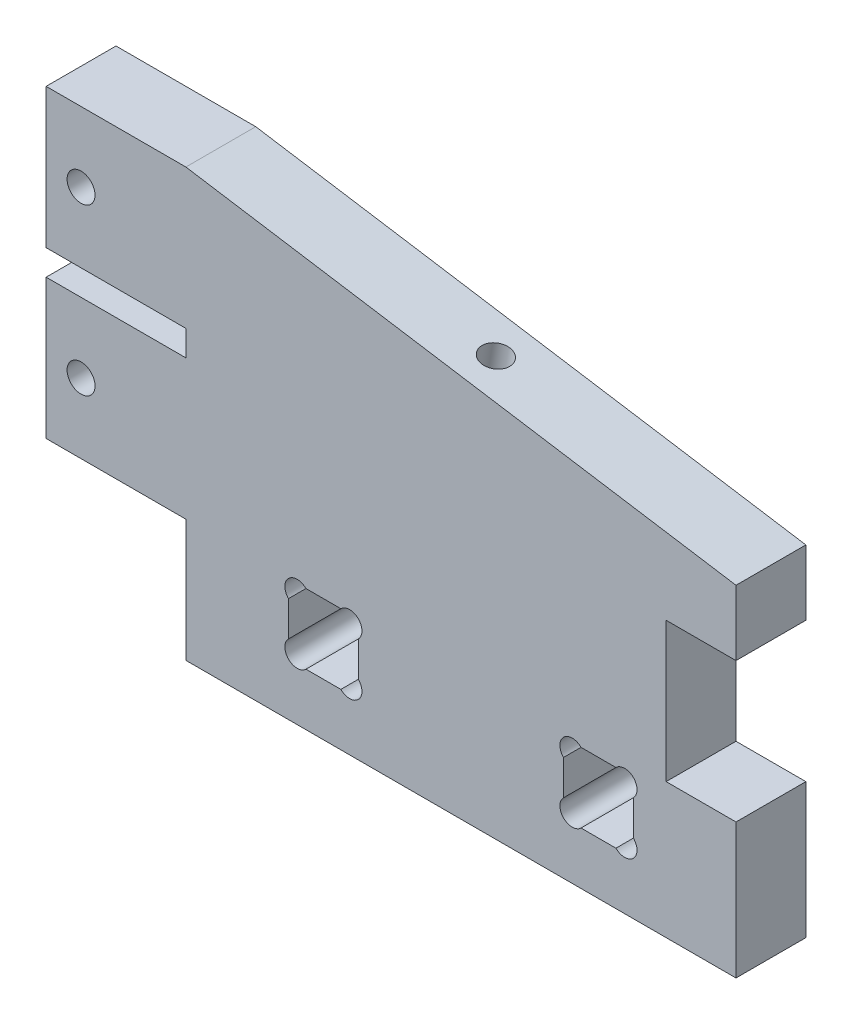
SolidWorks part; units mm, degrees
material "6061 Alloy"
ref_plane "Front" through (0, 0, 0) normal (0, 0, 1) x (1, 0, 0)
ref_plane "Top" through (0, 0, 0) normal (0, 1, 0) x (1, 0, 0)
ref_plane "Right" through (0, 0, 0) normal (1, 0, 0) x (0, 0, -1)
sketch "Sketch1" plane through (0, 0, 0) normal (0, 0, 1) x (1, 0, 0)
  line L0 (31.75, -68.1416) -> (31.75, -55.4412)
  line L1 (0, -55.4412) -> (31.75, -55.4412)
  line L2 (31.75, -68.1416) -> (131.75, -68.1416)
  line L3 (131.75, -68.1416) -> (131.75, -15.8384)
  line L4 (131.75, -15.8384) -> (31.75, 0)
  line L5 (0, -55.4412) -> (0, -30.0412)
  line L6 (0, -30.0412) -> (19.05, -30.0412)
  line L7 (31.75, 0) -> (19.05, 0)
  line L8 (19.05, -30.0412) -> (31.75, -30.0412)
  line L9 (19.05, -25.4) -> (0, -25.4)
  line L10 (19.05, 0) -> (0, 0)
  line L11 (0, -25.4) -> (0, 0)
  line L12 (31.75, -30.0412) -> (31.75, -25.4)
  line L13 (31.75, -25.4) -> (19.05, -25.4)
extrude "Boss-Extrude1" add sketch "Sketch1" along normal blind 12.7
sketch "Sketch2" plane through (0, 0, 12.7) normal (0, 0, 1) x (1, 0, 0)
  line L14 (19.05, 0) -> (19.05, -25.4) construction
  line L19 (0, -55.4412) -> (19.05, -55.4412)
  line L20 (0, -55.4412) -> (0, 0)
  line L21 (0, 0) -> (19.05, 0)
  line L23 (0, -25.4) -> (31.75, -25.4) construction
  line L24 (19.05, -12.7) -> (31.75, -12.7) construction
  line L25 (31.75, -27.7206) -> (0, -27.7206) construction
  line L26 (31.75, -25.4) -> (31.75, -30.0412) construction
  line L27 (19.05, 0) -> (19.05, -55.4412)
  circle A0 centre (25.4, -12.7) radius 2.54
  circle A1 centre (25.4, -42.7412) radius 2.54
  dimension "D1" = 5.08
extrude "Cut-Extrude2" cut sketch "Sketch2" against normal through all
sketch "Sketch3" plane through (0, 0, 12.7) normal (0, 0, 1) x (1, 0, 0)
  line L0 (131.75, -68.1416) -> (131.75, -15.8384) construction
  line L6 (31.75, -68.1412) -> (131.75, -68.1412)
  line L7 (31.75, -68.1412) -> (31.75, -81.0997)
  line L8 (31.75, -81.0997) -> (131.75, -81.0997)
  line L9 (131.75, -68.1412) -> (131.75, -81.0997)
extrude "Cut-Extrude3" cut sketch "Sketch3" against normal through all
sketch "Sketch5" plane through (0, 0, 12.7) normal (0, 0, 1) x (1, 0, 0)
  line L1 (31.75, -68.1412) -> (131.75, -68.1412)
  line L2 (31.75, -68.1412) -> (31.75, -77.6662)
  line L3 (31.75, -77.6662) -> (131.75, -77.6662)
  line L4 (131.75, -68.1412) -> (131.75, -77.6662)
  dimension "D1" = 9.525
extrude "Boss-Extrude3" add sketch "Sketch5" against normal up to surface (12.7 mm away) up to face at (45.3136, -33.9896, 0)
sketch "Sketch4" plane through (0, 0, 12.7) normal (0, 0, 1) x (1, 0, 0)
  line L6 (81.75, -58.6162) -> (81.75, -60.123) construction
  line L7 (56.75, -68.1412) -> (63.1, -68.1412)
  line L9 (56.75, -55.4412) -> (63.1, -55.4412)
  line L10 (63.1, -68.1412) -> (63.1, -55.4412)
  line L11 (56.75, -68.1412) -> (50.4, -68.1412)
  line L13 (56.75, -55.4412) -> (50.4, -55.4412)
  line L14 (50.4, -68.1412) -> (50.4, -55.4412)
  line L15 (106.75, -68.1412) -> (113.1, -68.1412)
  line L16 (113.1, -68.1412) -> (113.1, -55.4412)
  line L17 (106.75, -55.4412) -> (113.1, -55.4412)
  line L18 (106.75, -55.4412) -> (100.4, -55.4412)
  line L19 (100.4, -68.1412) -> (100.4, -55.4412)
  line L20 (106.75, -68.1412) -> (100.4, -68.1412)
  line L21 (56.75, -55.4412) -> (56.75, -68.1412) construction
  line L22 (56.75, -61.7912) -> (63.1, -61.7912) construction
  circle A0 centre (51.9875, -57.0287) radius 2.2454
  circle A1 centre (51.9875, -66.5537) radius 2.2454
  circle A2 centre (61.5125, -66.5537) radius 2.2454
  circle A3 centre (61.5125, -57.0287) radius 2.2454
  circle A4 centre (101.9875, -66.5537) radius 2.2454
  circle A5 centre (101.9875, -57.0287) radius 2.2454
  circle A6 centre (111.5125, -66.5537) radius 2.2454
  circle A7 centre (111.5125, -57.0287) radius 2.2454
  point P0 (31.75, -77.6662)
  dimension "D5" = 4.4907
  dimension "D1" = 9.525
  dimension "D2" = 12.7
  dimension "D3" = 6.35
  dimension "D4" = 6.35
  dimension "D6" = 1.5875
  dimension "D7" = 1.5875
extrude "Cut-Extrude4" cut sketch "Sketch4" against normal through all contours L13 A0 L14 | L14 A0 L13 | L10 A3 L9 L13 A0 L14 A1 L11 L7 A2 | A3 L10 L9 | L7 A2 L10 | A1 L11 L14 | L16 A7 L17 L18 A5 L19 A4 L20 L15 A6 | A1 L14 L11 | L10 A2 L7
sketch "Sketch6" plane through (0, 0, 12.7) normal (0, 0, 1) x (1, 0, 0)
  line L1 (19.05, -25.4) -> (6.35, -25.4)
  line L2 (19.05, -25.4) -> (19.05, 0)
  line L3 (19.05, 0) -> (6.35, 0)
  line L4 (6.35, -25.4) -> (6.35, 0)
  line L5 (19.05, -30.0412) -> (6.35, -30.0412)
  line L6 (19.05, -30.0412) -> (19.05, -55.4412)
  line L7 (19.05, -55.4412) -> (6.35, -55.4412)
  line L8 (6.35, -30.0412) -> (6.35, -55.4412)
  circle A0 centre (25.4, -12.7) radius 4.0913
  circle A1 centre (25.4, -42.7412) radius 6.0524
  dimension "D1" = 12.7
  dimension "D2" = 12.7
extrude "Boss-Extrude4" add sketch "Sketch6" against normal up to surface (12.7 mm away) up to face at (56.75, -61.7912, 0)
sketch "Sketch7" plane through (0, 0, 12.7) normal (0, 0, 1) x (1, 0, 0)
  line L0 (6.35, -25.4) -> (19.05, -25.4) construction
  line L1 (6.35, -25.4) -> (31.75, -25.4) construction
  line L2 (12.7, -25.4) -> (12.7, 0) construction
  line L3 (31.75, 0) -> (6.35, 0) construction
  line L4 (31.75, -27.7206) -> (-8.6786, -27.7206) construction
  line L5 (31.75, -25.4) -> (31.75, -30.0412) construction
  circle A0 centre (12.7, -12.7) radius 2.54
  circle A1 centre (12.7, -42.7412) radius 2.54
  dimension "D1" = 5.08
extrude "Cut-Extrude5" cut sketch "Sketch7" against normal through all
sketch "Sketch8" plane through (0, 0, 12.7) normal (0, 0, 1) x (1, 0, 0)
  line L0 (131.75, -15.8384) -> (131.75, -77.6662) construction
  line L3 (131.75, -46.7523) -> (131.75, -27.7023)
  line L4 (131.75, -27.7023) -> (119.05, -27.7023)
  line L5 (119.05, -46.7523) -> (119.05, -27.7023)
  line L7 (119.05, -46.7523) -> (119.05, -53.1023)
  line L8 (119.05, -53.1023) -> (131.75, -53.1023)
  line L9 (131.75, -46.7523) -> (131.75, -53.1023)
  dimension "D1" = 12.7
  dimension "D2" = 19.05
  dimension "D3" = 6.35
extrude "Cut-Extrude6" cut sketch "Sketch8" against normal through all contours L5 L4 L3 L9 L8 L7
sketch "Sketch9" plane through (0.777, 4.9056, 0) normal (0.1564, 0.9877, 0) x (0.9877, -0.1564, 0)
  line L0 (31.3591, -6.35) -> (132.6056, -6.35) construction
  line L1 (31.3591, -12.7) -> (31.3591, 0) construction
  line L2 (132.6056, -12.7) -> (132.6056, 0) construction
  circle A0 centre (81.9824, -6.35) radius 2.54
  dimension "D1" = 5.08
extrude "Cut-Extrude7" cut sketch "Sketch9" against normal blind 9.525
